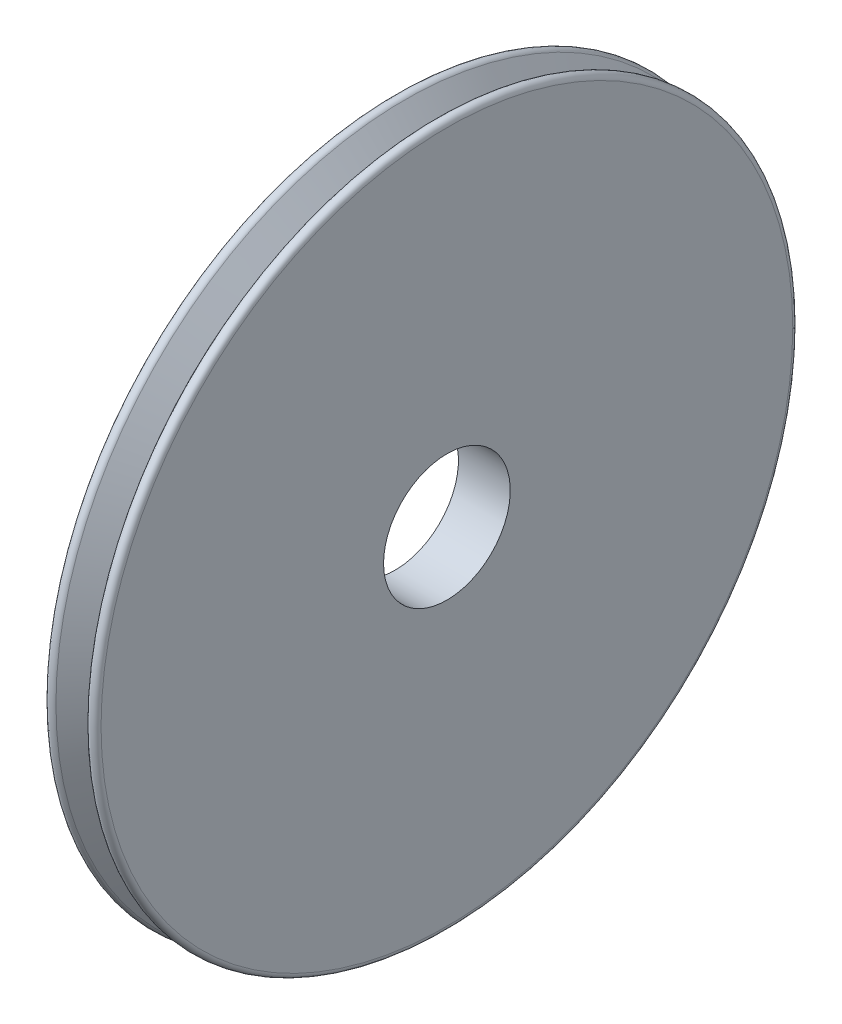
SolidWorks part; units mm, degrees
ref_plane "Front Plane" through (0, 0, 0) normal (0, 0, 1) x (1, 0, 0)
ref_plane "Top Plane" through (0, 0, 0) normal (0, 1, 0) x (1, 0, 0)
ref_plane "Right Plane" through (0, 0, 0) normal (1, 0, 0) x (0, 0, -1)
sketch "Sketch1" plane through (0, 0, 0) normal (0, 0, 1) x (1, 0, 0)
  line L0 (0, 0) -> (0, 63.1756) construction
  line L1 (-3.57, 0) -> (3.57, 0)
  line L2 (3.57, 0) -> (3.57, 50)
  line L3 (3.57, 50) -> (0, 45)
  line L4 (0, 45) -> (0, 0)
  line L5 (-3.57, 50) -> (0, 45)
  line L6 (-3.57, 0) -> (-3.57, 50)
  line L7 (0, 0) -> (65.8087, 0) construction
  dimension "D1" = 3.57
  dimension "D2" = 50
  dimension "D3" = 45
revolve "Revolve1" add sketch "Sketch1" angle 360 about L7
fillet "Fillet1" radius 0.75 2 edges at (-3.57, 0, 50) (3.57, 0, 50)
sketch "Sketch2" plane through (0, 0, 0) normal (1, 0, 0) x (0, 0, -1)
  circle A0 centre (0, 0) radius 8.73
  dimension "D1" = 17.46
extrude "Cut-Extrude1" cut sketch "Sketch2" against normal mid plane 10
